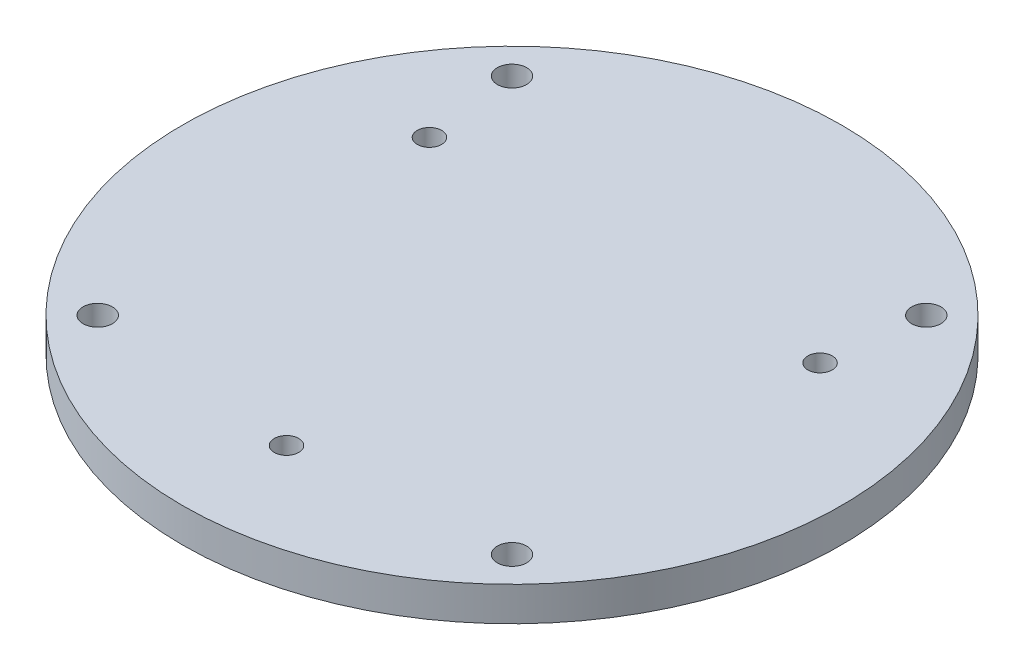
SolidWorks part; units mm, degrees
material "1060 Alloy"
ref_plane "Front Plane" through (0, 0, 0) normal (0, 0, 1) x (1, 0, 0)
ref_plane "Top Plane" through (0, 0, 0) normal (0, 1, 0) x (1, 0, 0)
ref_plane "Right Plane" through (0, 0, 0) normal (1, 0, 0) x (0, 0, -1)
sketch "Sketch1" plane through (0, 0, 0) normal (0, 1, 0) x (1, 0, 0)
  line L0 (0, 0) -> (-40, 23.094) construction
  line L1 (0, 0) -> (40, 23.094) construction
  line L2 (0, 0) -> (0, -46.188) construction
  line L3 (0, 46.6256) -> (0, 0) construction
  circle A0 centre (-40, 23.094) radius 2.5
  circle A1 centre (40, 23.094) radius 2.5
  circle A2 centre (0, -46.188) radius 2.5
  circle A3 centre (0, 0) radius 67.5
  dimension "D4" = 5
  dimension "D5" = 5
  dimension "D9" = 135
  dimension "D10" = 5
  dimension "D1" = 60
  dimension "D2" = 60
  dimension "D3" = 120
  dimension "D6" = 80
  dimension "D7" = 80
  dimension "D8" = 80
extrude "Boss-Extrude1" add sketch "Sketch1" along normal blind 7
sketch "Sketch3" plane through (0, 7, 0) normal (0, 1, 0) x (1, 0, 0)
  circle A0 centre (42.425, 42.425) radius 3
  circle A1 centre (42.425, -42.425) radius 3
  circle A2 centre (-42.425, -42.425) radius 3
  circle A3 centre (-42.425, 42.425) radius 3
  point P0 (0, 0)
  dimension "D1" = 84.85
  dimension "D3" = 6
  dimension "D2" = 84.85
extrude "Cut-Extrude1" cut sketch "Sketch3" against normal blind 10
